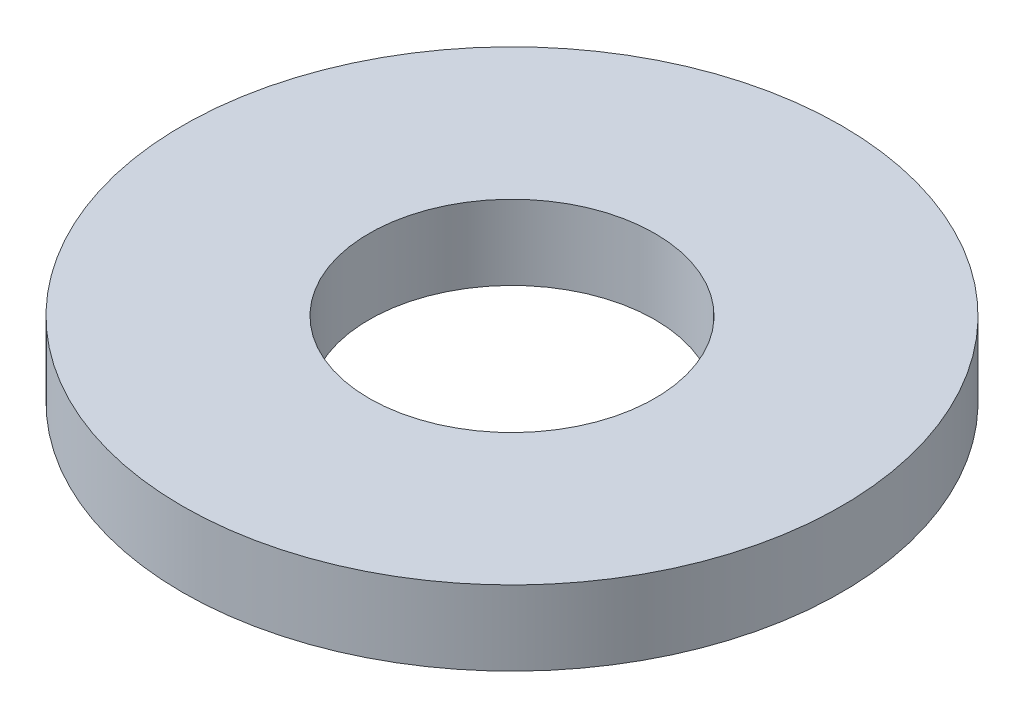
SolidWorks part; units mm, degrees
material "Copper"
ref_plane "Front Plane" through (0, 0, 0) normal (0, 0, 1) x (1, 0, 0)
ref_plane "Top Plane" through (0, 0, 0) normal (0, 1, 0) x (1, 0, 0)
ref_plane "Right Plane" through (0, 0, 0) normal (1, 0, 0) x (0, 0, -1)
sketch "Sketch1" plane through (0, 0, 0) normal (0, 1, 0) x (1, 0, 0)
  circle A0 centre (0, 0) radius 29.71
  circle A1 centre (0, 0) radius 68.52
  dimension "D1" = 59.42
  dimension "D2" = 38.81
extrude "Extrude1" add sketch "Sketch1" along normal blind 15.524
